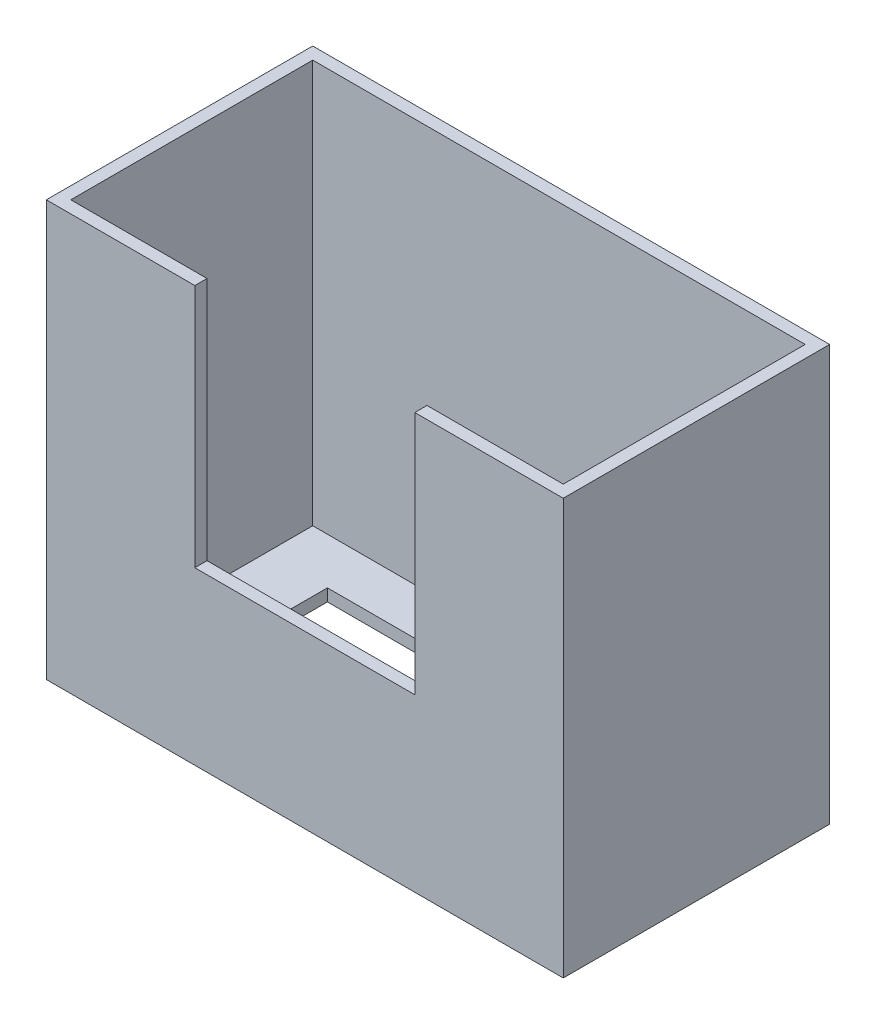
SolidWorks part; units mm, degrees
ref_plane "Front Plane" through (0, 0, 0) normal (0, 0, 1) x (1, 0, 0)
ref_plane "Top Plane" through (0, 0, 0) normal (0, 1, 0) x (1, 0, 0)
ref_plane "Right Plane" through (0, 0, 0) normal (1, 0, 0) x (0, 0, -1)
sketch "Sketch6" plane through (0, 0, 0) normal (0, 1, 0) x (1, 0, 0)
  line L1 (0, 0) -> (201.5, 0)
  line L2 (0, 0) -> (0, 99)
  line L3 (0, 99) -> (201.5, 99)
  line L4 (201.5, 0) -> (201.5, 99)
  dimension "D1" = 99
  dimension "D2" = 201.5
extrude "Boss-Extrude1" add sketch "Sketch6" along normal blind 165
shell "Shell1" thickness 5
sketch "Sketch7" plane through (0, 0, 0) normal (0, 1, 0) x (1, 0, 0)
  line L0 (0, 0) -> (201.5, 0) construction
  line L1 (25, 80) -> (175, 80)
  line L2 (25, 80) -> (25, 40)
  line L3 (25, 40) -> (175, 40)
  line L4 (175, 80) -> (175, 40)
  line L5 (25, 80) -> (175, 40) construction
  line L6 (25, 40) -> (175, 80) construction
  line L8 (0, 99) -> (0, 0) construction
  point P0 (100, 60)
  point P7 (100.75, 0)
  dimension "D1" = 60
  dimension "D2" = 40
  dimension "D3" = 150
  dimension "D4" = 100
extrude "Cut-Extrude1" cut sketch "Sketch7" against normal blind 165
sketch "Sketch8" plane through (0, 0, 5) normal (0, 0, 1) x (1, 0, 0)
  line L0 (100.75, 165) -> (100.75, -5) construction
  line L1 (-5, 165) -> (206.5, 165) construction
  line L2 (-5, -5) -> (206.5, -5) construction
  line L3 (55.75, 165) -> (145.75, 165)
  line L4 (55.75, 165) -> (55.75, 65)
  line L5 (145.75, 165) -> (145.75, 65)
  line L6 (55.75, 65) -> (145.75, 65)
  point P6 (100.75, 65)
  point P8 (100.75, 165)
  dimension "D1" = 90
  dimension "D2" = 100
extrude "Cut-Extrude2" cut sketch "Sketch8" against normal up to next
